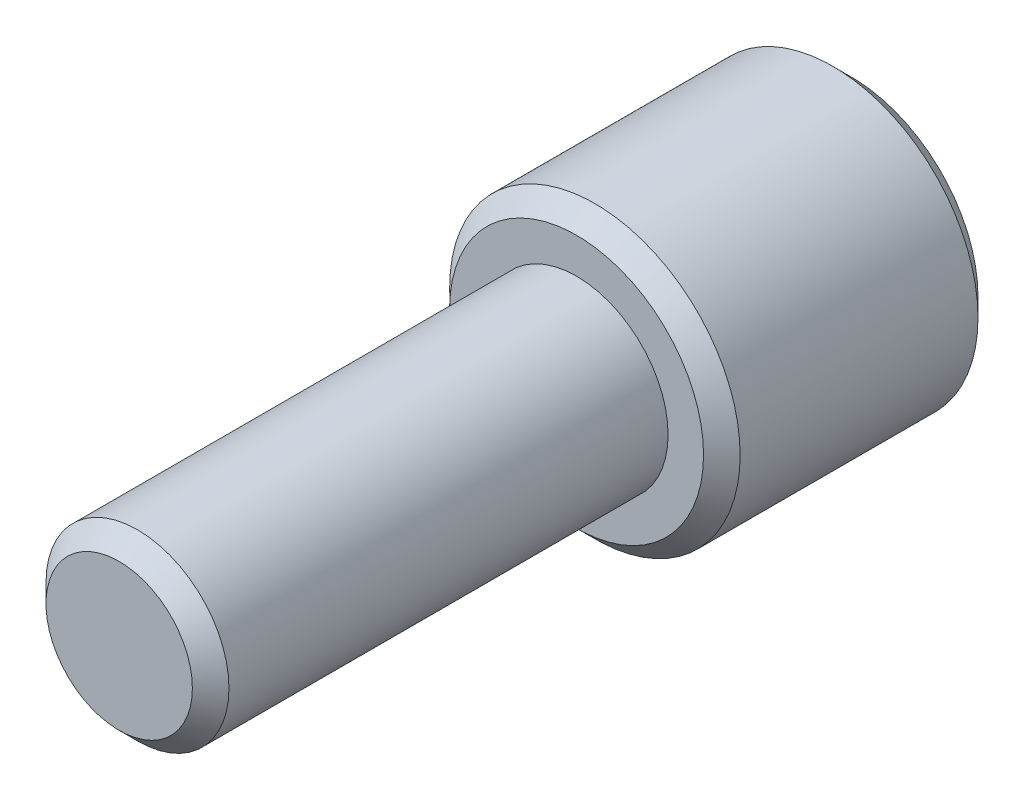
SolidWorks part; units mm, degrees
ref_plane "Alzado" through (0, 0, 0) normal (0, 0, 1) x (1, 0, 0)
ref_plane "Planta" through (0, 0, 0) normal (0, 1, 0) x (1, 0, 0)
ref_plane "Vista lateral" through (0, 0, 0) normal (1, 0, 0) x (0, 0, -1)
sketch "Croquis1" plane through (0, 0, 0) normal (0, 0, 1) x (1, 0, 0)
  circle A0 centre (0, 0) radius 6.35
  dimension "D1" = 12.7
extrude "Saliente-Extruir1" add sketch "Croquis1" along normal blind 12
sketch "Croquis2" plane through (0, 0, 12) normal (0, 0, 1) x (1, 0, 0)
  circle A0 centre (0, 0) radius 4
  dimension "D1" = 8
extrude "Saliente-Extruir2" add sketch "Croquis2" along normal blind 20
sketch "Croquis3" plane through (0, 0, 0) normal (0, 0, -1) x (-1, 0, 0)
  circle A0 centre (0, 0) radius 2.5
  dimension "D1" = 5
extrude "Cortar-Extruir1" cut sketch "Croquis3" against normal blind 10
sketch "Croquis4" plane through (0, 0, 0) normal (1, 0, 0) x (0, 0, -1)
  line L0 (0, 0) -> (-12, 0) construction
  line L1 (-12, 4) -> (-12, -4) construction
  circle A0 centre (-6, 0) radius 2
  dimension "D1" = 4
extrude "Cortar-Extruir2" cut sketch "Croquis4" against normal through all
sketch "Croquis5" plane through (0, 0, 0) normal (0, 1, 0) x (1, 0, 0)
  line L0 (0, 0) -> (0, -12) construction
  line L1 (-6.35, -12) -> (6.35, -12) construction
  circle A0 centre (0, -6) radius 2
  dimension "D1" = 4
extrude "Cortar-Extruir3" cut sketch "Croquis5" against normal through all
chamfer "Chaflán1" distance 0.8 angle 45 3 edges at (4, 0, 32) (6.35, 0, 12) (6.35, 0, 0)
